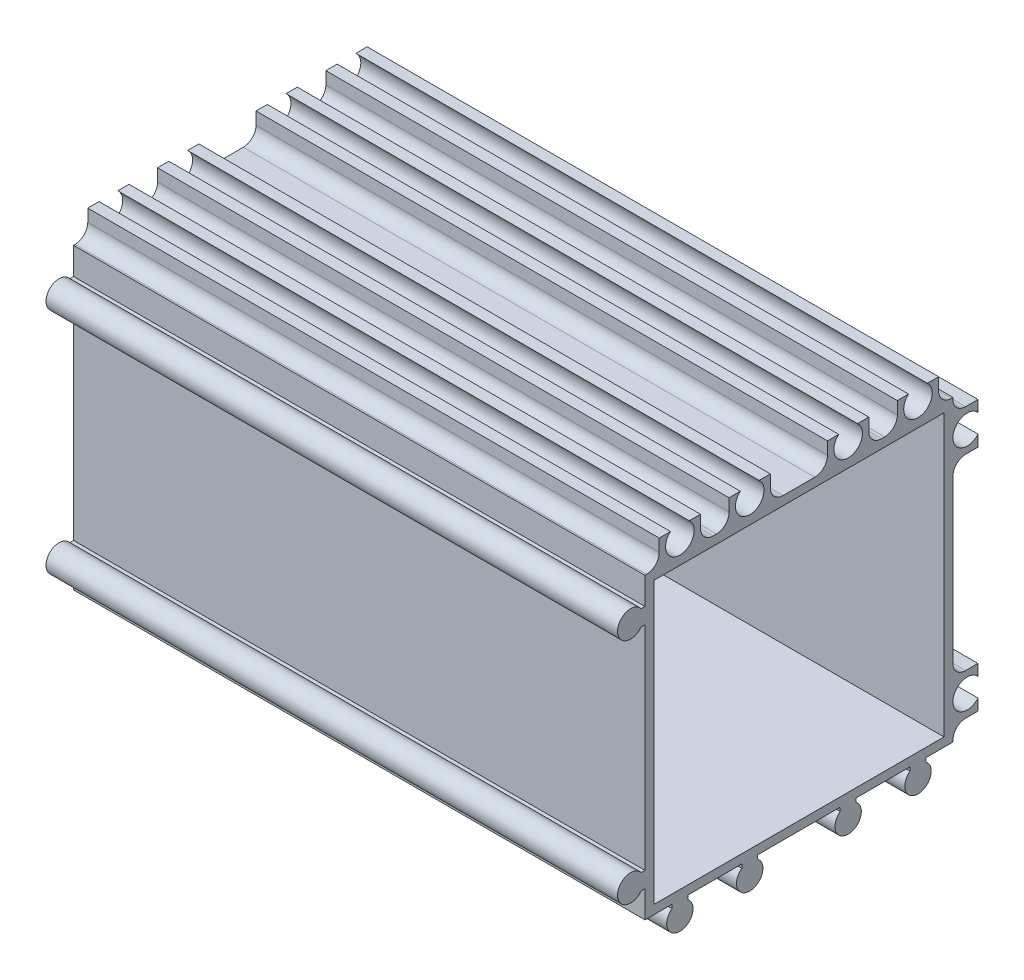
SolidWorks part; units mm, degrees
ref_plane "Спереди" through (0, 0, 0) normal (0, 0, 1) x (1, 0, 0)
ref_plane "Сверху" through (0, 0, 0) normal (0, 1, 0) x (1, 0, 0)
ref_plane "Справа" through (0, 0, 0) normal (1, 0, 0) x (0, 0, -1)
ref_plane "Плоскость4" through (90, 0, 0) normal (1, 0, 0) x (0, 0, -1)
sketch "Эскиз1" plane through (90, 0, 0) normal (1, 0, 0) x (0, 0, -1)
  line L0 (6.75, 160.9062) -> (6.75, 204.25)
  line L1 (6.75, 204.25) -> (-38.0938, 204.25)
  line L2 (-38.0938, 201.75) -> (-37.5, 201.75)
  line L3 (-37.5, 201.75) -> (-37.5, 168.25)
  line L4 (-37.5, 168.25) -> (-38.0938, 168.25)
  line L5 (-38.0938, 165.75) -> (-37.5, 165.75)
  line L6 (-37.5, 165.75) -> (-37.5, 161.5)
  line L7 (-37.5, 161.5) -> (-33.25, 161.5)
  line L8 (-33.25, 161.5) -> (-33.25, 160.9062)
  line L9 (-30.75, 160.9062) -> (-30.75, 161.5)
  line L10 (-30.75, 161.5) -> (-22.25, 161.5)
  line L11 (-22.25, 161.5) -> (-22.25, 160.9062)
  line L12 (-19.75, 160.9062) -> (-19.75, 161.5)
  line L13 (-19.75, 161.5) -> (-6.75, 161.5)
  line L14 (-6.75, 161.5) -> (-6.75, 160.9062)
  line L15 (-4.25, 160.9062) -> (-4.25, 161.5)
  line L16 (-4.25, 161.5) -> (4.25, 161.5)
  line L17 (4.25, 161.5) -> (4.25, 160.9062)
  arc A0 (-38.0938, 204.25) -> (-38.0938, 201.75) centre (-39.75, 203) ccw
  arc A1 (-38.0938, 168.25) -> (-38.0938, 165.75) centre (-39.75, 167) ccw
  arc A2 (-33.25, 160.9062) -> (-30.75, 160.9062) centre (-32, 159.25) ccw
  arc A3 (-22.25, 160.9062) -> (-19.75, 160.9062) centre (-21, 159.25) ccw
  arc A4 (-6.75, 160.9062) -> (-4.25, 160.9062) centre (-5.5, 159.25) ccw
  arc A5 (4.25, 160.9062) -> (6.75, 160.9062) centre (5.5, 159.25) ccw
extrude "Бобышка-Вытянуть1" add sketch "Эскиз1" against normal blind 90
sketch "Эскиз2" plane through (0, 0, -6.75) normal (0, 0, -1) x (-1, 0, 0)
  line L0 (0, 204.25) -> (0, 161.5)
  line L1 (0, 161.5) -> (-90, 161.5)
  line L2 (-90, 161.5) -> (-90, 204.25)
  line L3 (-90, 204.25) -> (0, 204.25)
extrude "Бобышка-Вытянуть2" add sketch "Эскиз2" along normal blind 8.2
sketch "Эскиз3" plane through (0, 204.25, 0) normal (0, 1, 0) x (-1, 0, 0)
  line L0 (-90, -14.95) -> (-90, 37.5)
  line L1 (-90, 37.5) -> (0, 37.5)
  line L2 (0, 37.5) -> (0, -14.95)
  line L3 (0, -14.95) -> (-90, -14.95)
extrude "Бобышка-Вытянуть3" add sketch "Эскиз3" along normal blind 8.2
sketch "Эскиз4" plane through (0, 0, 0) normal (-1, 0, 0) x (0, 0, 1)
  line L0 (-14.95, 161.5) -> (-11, 161.5)
  line L1 (-11, 161.5) -> (-11, 163.75)
  line L2 (-11, 163.75) -> (-14.95, 163.75)
  line L3 (-14.95, 163.75) -> (-14.95, 161.5)
extrude "Вырез-Вытянуть1" cut sketch "Эскиз4" against normal through all
sketch "Эскиз5" plane through (0, 0, 0) normal (-1, 0, 0) x (0, 0, 1)
  line L0 (-14.95, 170.25) -> (-11, 170.25)
  line L1 (-11, 170.25) -> (-11, 199.75)
  line L2 (-11, 199.75) -> (-14.95, 199.75)
  line L3 (-14.95, 199.75) -> (-14.95, 170.25)
extrude "Вырез-Вытянуть2" cut sketch "Эскиз5" against normal through all
sketch "Эскиз6" plane through (0, 0, 0) normal (-1, 0, 0) x (0, 0, 1)
  line L0 (-14.95, 212.45) -> (-14.95, 206.25)
  line L1 (-14.95, 206.25) -> (-11, 206.25)
  line L2 (-11, 206.25) -> (-11, 212.45)
  line L3 (-11, 212.45) -> (-14.95, 212.45)
extrude "Вырез-Вытянуть3" cut sketch "Эскиз6" against normal through all
sketch "Эскиз7" plane through (0, 0, 0) normal (-1, 0, 0) x (0, 0, 1)
  line L0 (-11, 212.45) -> (-11, 208.5)
  line L1 (-11, 208.5) -> (-8.75, 208.5)
  line L2 (-8.75, 208.5) -> (-8.75, 212.45)
  line L3 (-8.75, 212.45) -> (-11, 212.45)
extrude "Вырез-Вытянуть4" cut sketch "Эскиз7" against normal through all
sketch "Эскиз8" plane through (0, 0, 0) normal (-1, 0, 0) x (0, 0, 1)
  line L0 (-2.25, 212.45) -> (-2.25, 208.5)
  line L1 (-2.25, 208.5) -> (2.25, 208.5)
  line L2 (2.25, 208.5) -> (2.25, 212.45)
  line L3 (2.25, 212.45) -> (-2.25, 212.45)
extrude "Вырез-Вытянуть5" cut sketch "Эскиз8" against normal through all
sketch "Эскиз9" plane through (0, 0, 0) normal (-1, 0, 0) x (0, 0, 1)
  line L0 (8.75, 212.45) -> (8.75, 208.5)
  line L1 (8.75, 208.5) -> (17.75, 208.5)
  line L2 (17.75, 208.5) -> (17.75, 212.45)
  line L3 (17.75, 212.45) -> (8.75, 212.45)
extrude "Вырез-Вытянуть6" cut sketch "Эскиз9" against normal through all
sketch "Эскиз10" plane through (0, 0, 0) normal (-1, 0, 0) x (0, 0, 1)
  line L0 (24.25, 212.45) -> (24.25, 208.5)
  line L1 (24.25, 208.5) -> (28.75, 208.5)
  line L2 (28.75, 208.5) -> (28.75, 212.45)
  line L3 (28.75, 212.45) -> (24.25, 212.45)
extrude "Вырез-Вытянуть7" cut sketch "Эскиз10" against normal through all
sketch "Эскиз11" plane through (0, 0, 0) normal (-1, 0, 0) x (0, 0, 1)
  line L0 (37.5, 212.45) -> (35.25, 212.45)
  line L1 (35.25, 212.45) -> (35.25, 208.5)
  line L2 (35.25, 208.5) -> (37.5, 208.5)
  line L3 (37.5, 208.5) -> (37.5, 212.45)
extrude "Вырез-Вытянуть8" cut sketch "Эскиз11" against normal through all
sketch "Эскиз12" plane through (90, 0, 0) normal (1, 0, 0) x (0, 0, -1)
  line L0 (9.6, 207.1) -> (-36.1, 207.1)
  line L1 (-36.1, 207.1) -> (-36.1, 162.9)
  line L2 (-36.1, 162.9) -> (9.6, 162.9)
  line L3 (9.6, 162.9) -> (9.6, 207.1)
extrude "Вырез-Вытянуть9" cut sketch "Эскиз12" against normal blind 86
hole_wizard "Диаметр отверстия Ø2.5 (2.5)1" positions "Эскиз14" profile "Эскиз13" hole size "Ø2.5" standard "Ansi Metric"
sketch "Эскиз14" plane through (90, 0, 0) normal (1, 0, 0) x (0, 0, -1)
  point P0 (5.5, 159.25)
  point P1 (-21, 159.25)
  point P2 (-5.5, 159.25)
  point P3 (-32, 159.25)
  point P4 (-39.75, 167)
  point P5 (-39.75, 203)
sketch "Эскиз13" plane through (90, 159.25, -5.5) normal (0, 1, 0) x (0, 0, -1)
  line L0 (0, 0) -> (0, 90)
  line L1 (0, 90) -> (1.25, 90)
  line L2 (1.25, 90) -> (1.25, 0)
  line L5 (1.25, 0) -> (0, 0)
  line L11 (0, -6.35) -> (0, 107.95) construction
  dimension "Диаметр сквозного отверстия" = 2.5
  dimension "Глубина сквозного отверстия" = 90
hole_wizard "Диаметр отверстия Ø4.5 (4.5)1" positions "Эскиз16" profile "Эскиз15" hole size "Ø4.5" standard "Ansi Metric"
sketch "Эскиз16" plane through (0, 0, 0) normal (-1, 0, 0) x (0, 0, 1)
  point P0 (-13.25, 167)
  point P1 (-13.25, 203)
  point P2 (-5.5, 210.75)
  point P3 (5.5, 210.75)
  point P4 (21, 210.75)
  point P5 (32, 210.75)
sketch "Эскиз15" plane through (0, 167, -13.25) normal (0, 1, 0) x (0, 0, 1)
  line L0 (0, 0) -> (0, 90)
  line L1 (0, 90) -> (2.25, 90)
  line L2 (2.25, 90) -> (2.25, 0)
  line L5 (2.25, 0) -> (0, 0)
  line L11 (0, -6.35) -> (0, 107.95) construction
  dimension "Диаметр сквозного отверстия" = 4.5
  dimension "Глубина сквозного отверстия" = 90
hole_wizard "Диаметр отверстия Ø8.3 (8.3)1" positions "Эскиз18" profile "Эскиз17" hole size "Ø8.3" standard "Ansi Metric"
sketch "Эскиз18" plane through (0, 0, 0) normal (-1, 0, 0) x (0, 0, 1)
  point P0 (13.25, 185)
sketch "Эскиз17" plane through (0, 185, 13.25) normal (0, 1, 0) x (0, 0, 1)
  line L0 (0, 0) -> (0, 3.2)
  line L1 (0, 3.2) -> (4.15, 3.2)
  line L2 (4.15, 3.2) -> (4.15, 0)
  line L5 (4.15, 0) -> (0, 0)
  line L10 (0, 3.2) -> (-4.15, 3.2) construction
  line L11 (0, -6.35) -> (0, 107.95) construction
  dimension "Диаметр отверстия" = 8.3
  dimension "Глубина отверстия" = 3.2
  dimension "Угол заточки сверла" = 180
sketch "Эскиз19" plane through (90, 0, 0) normal (1, 0, 0) x (0, 0, -1)
  circle A0 centre (-39.75, 203) radius 1.6725
  circle A1 centre (-39.75, 167) radius 1.4592
  circle A2 centre (-32, 159.25) radius 1.4599
  circle A3 centre (-21, 159.25) radius 1.5928
  circle A4 centre (-5.5, 159.25) radius 1.5322
  circle A5 centre (5.5, 159.25) radius 1.5961
extrude "Бобышка-Вытянуть4" add sketch "Эскиз19" against normal blind 90
sketch "Эскиз20" plane through (0, 0, 0) normal (-1, 0, 0) x (0, 0, 1)
  circle A0 centre (13.25, 185) radius 4.15
extrude "Вырез-Вытянуть10" cut sketch "Эскиз20" against normal blind 90
fillet "Скругление1" radius 2 1 edges at (45, 208.5, -8.75)
fillet "Скругление2" radius 2 1 edges at (45, 163.75, -11)
fillet "Скругление3" radius 2 1 edges at (45, 170.25, -11)
fillet "Скругление4" radius 2 1 edges at (45, 199.75, -11)
fillet "Скругление5" radius 2 1 edges at (45, 206.25, -11)
fillet "Скругление6" radius 2 1 edges at (45, 208.5, -2.25)
fillet "Скругление7" radius 2 1 edges at (45, 208.5, 2.25)
fillet "Скругление8" radius 2 1 edges at (45, 208.5, 8.75)
fillet "Скругление9" radius 2 1 edges at (45, 208.5, 17.75)
fillet "Скругление10" radius 2 1 edges at (45, 208.5, 24.25)
fillet "Скругление11" radius 2 1 edges at (45, 208.5, 28.75)
fillet "Скругление12" radius 2 1 edges at (45, 208.5, 35.25)
fillet "Скругление13" radius 1.2 4 edges at (4, 185, -9.6) (4, 162.9, 13.25) (4, 185, 36.1) (4, 207.1, 13.25)
